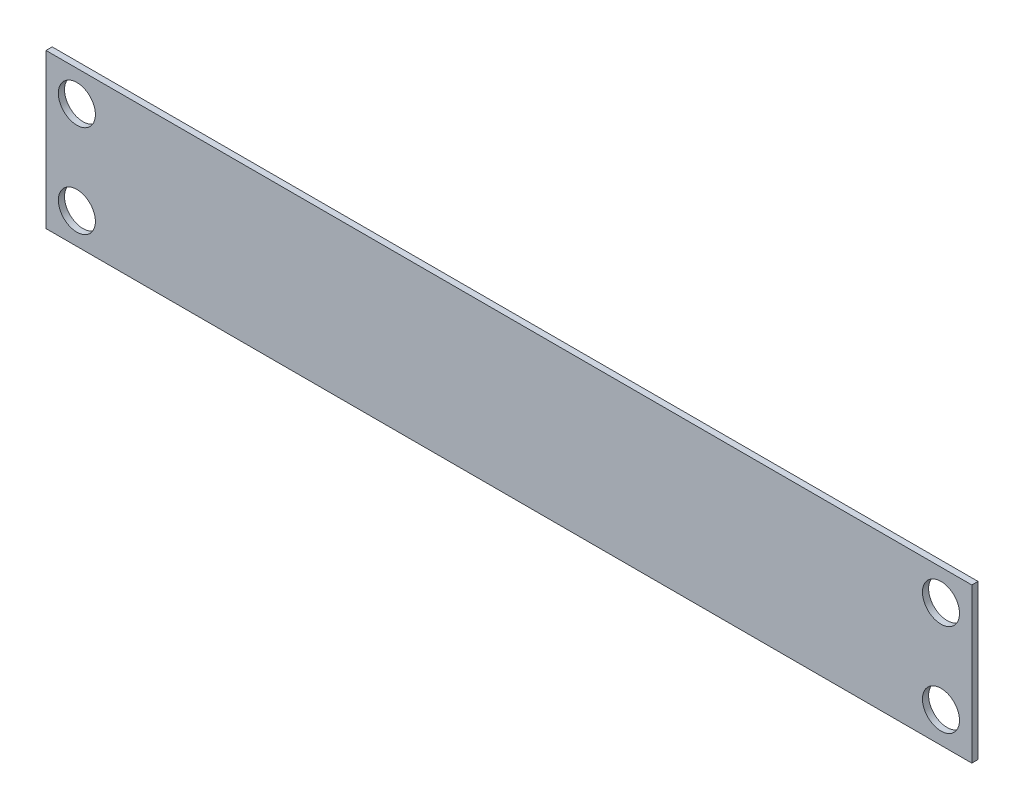
SolidWorks part; units mm, degrees
ref_plane "Alzado" through (0, 0, 0) normal (0, 0, 1) x (1, 0, 0)
ref_plane "Planta" through (0, 0, 0) normal (0, 1, 0) x (1, 0, 0)
ref_plane "Vista lateral" through (0, 0, 0) normal (1, 0, 0) x (0, 0, -1)
sketch "Croquis1" plane through (0, 0, 0) normal (0, 0, 1) x (1, 0, 0)
  line L1 (-150, -25) -> (150, -25)
  line L2 (-150, -25) -> (-150, 25)
  line L3 (-150, 25) -> (150, 25)
  line L4 (150, -25) -> (150, 25)
  line L5 (-150, -25) -> (150, 25) construction
  line L6 (-150, 25) -> (150, -25) construction
  point P0 (0, 0)
  dimension "D1" = 50
  dimension "D2" = 300
extrude "Saliente-Extruir1" add sketch "Croquis1" along normal blind 2
sketch "Croquis2" plane through (0, 0, 2) normal (0, 0, 1) x (1, 0, 0)
  line L0 (-150, -25) -> (150, -25) construction
  line L1 (-150, 25) -> (-150, -25) construction
  circle A0 centre (-140, -15) radius 6
  dimension "D1" = 12
  dimension "D2" = 10
  dimension "D3" = 10
extrude "Cortar-Extruir1" cut sketch "Croquis2" against normal through all
mirror "Simetría1" about plane through (0, 0, 0) normal (0, 1, 0) of "Cortar-Extruir1"
mirror "Simetría2" about plane through (0, 0, 0) normal (1, 0, 0) of "Cortar-Extruir1", "Simetría1"
